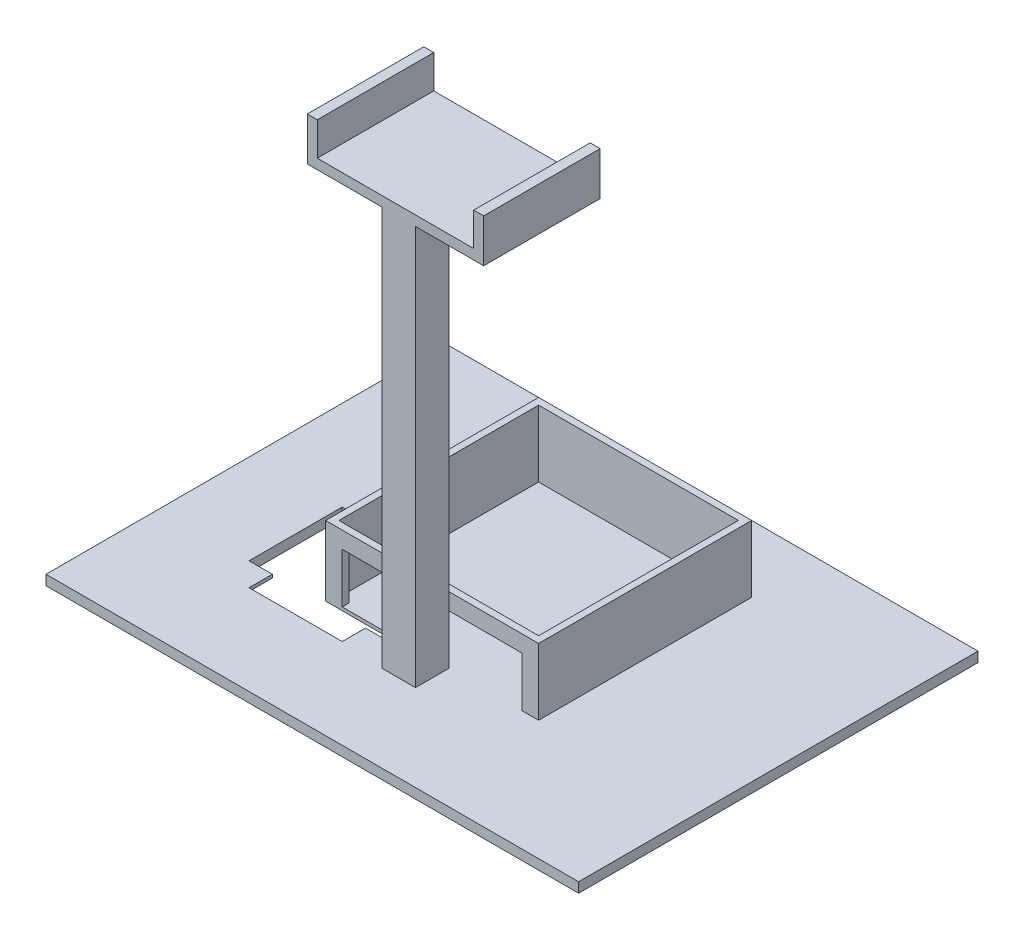
SolidWorks part; units mm, degrees
ref_plane "Front Plane" through (0, 0, 0) normal (0, 0, 1) x (1, 0, 0)
ref_plane "Top Plane" through (0, 0, 0) normal (0, 1, 0) x (1, 0, 0)
ref_plane "Right Plane" through (0, 0, 0) normal (1, 0, 0) x (0, 0, -1)
sketch "Sketch1" plane through (0, 0, 0) normal (0, 1, 0) x (1, 0, 0)
  line L1 (-80, -60) -> (80, -60)
  line L2 (-80, -60) -> (-80, 60)
  line L3 (-80, 60) -> (80, 60)
  line L4 (80, -60) -> (80, 60)
  line L5 (-80, -60) -> (80, 60) construction
  line L6 (-80, 60) -> (80, -60) construction
  point P0 (0, 0)
  dimension "D1" = 160
  dimension "D2" = 120
extrude "Boss-Extrude1" add sketch "Sketch1" along normal blind 3
sketch "Sketch2" plane through (0, 0, 0) normal (0, -1, 0) x (1, 0, 0)
  line L0 (0, 60) -> (0, 50) construction
  line L1 (-80, 60) -> (80, 60) construction
  line L2 (80, 60) -> (80, 50) construction
  line L3 (80, 60) -> (80, -60) construction
  line L4 (80, 50) -> (70, 50) construction
  line L5 (-80, 60) -> (-80, 50) construction
  line L6 (-80, -60) -> (-80, 60) construction
  line L7 (-80, 50) -> (-70, 50) construction
  line L8 (-80, 0) -> (-70, 0) construction
  line L9 (-80, -60) -> (-70, -60) construction
  line L10 (80, -60) -> (-80, -60) construction
  line L11 (-70, -60) -> (-70, -50) construction
  line L12 (80, 0) -> (70, 0) construction
  line L13 (80, -60) -> (70, -60) construction
  line L14 (70, -60) -> (70, -50) construction
  line L15 (0, -60) -> (0, -50) construction
  circle A0 centre (-70, 50) radius 5
  circle A1 centre (0, 50) radius 5
  circle A2 centre (70, 50) radius 5
  circle A3 centre (-70, 0) radius 5
  circle A4 centre (70, 0) radius 5
  circle A5 centre (-70, -50) radius 5
  circle A6 centre (0, -50) radius 5
  circle A7 centre (70, -50) radius 5
  dimension "D12" = 10
  dimension "D13" = 10
  dimension "D14" = 10
  dimension "D15" = 10
  dimension "D16" = 10
  dimension "D17" = 10
  dimension "D18" = 10
  dimension "D19" = 10
  dimension "D20" = 10
  dimension "D1" = 10
  dimension "D2" = 10
  dimension "D3" = 10
  dimension "D4" = 10
  dimension "D5" = 10
  dimension "D6" = 10
  dimension "D7" = 10
  dimension "D8" = 10
  dimension "D9" = 10
  dimension "D10" = 10
  dimension "D11" = 10
extrude "Cut-Extrude1" cut sketch "Sketch2" against normal blind 2
sketch "Sketch3" plane through (0, 0, 0) normal (0, -1, 0) x (1, 0, 0)
  line L0 (-80, 60) -> (-53, 60) construction
  line L1 (-80, 60) -> (80, 60) construction
  line L2 (-53, 60) -> (-53, 33) construction
  line L4 (-53, 33) -> (-11, 33)
  line L5 (-53, 33) -> (-53, -9)
  line L6 (-53, -9) -> (-11, -9)
  line L7 (-11, 33) -> (-11, -9)
  dimension "D1" = 27
  dimension "D2" = 27
  dimension "D3" = 42
  dimension "D4" = 42
extrude "Cut-Extrude2" cut sketch "Sketch3" against normal blind 2
sketch "Sketch4" plane through (0, 2, 0) normal (0, -1, 0) x (1, 0, 0)
  line L0 (-46, 33) -> (-18, 33)
  line L1 (-11, 33) -> (-53, 33) construction
  line L2 (-11, 33) -> (-53, 33) construction
  line L3 (-18, 33) -> (-18, 26)
  line L4 (-18, 26) -> (-11, 26)
  line L5 (-11, -9) -> (-11, 33) construction
  line L6 (-11, 26) -> (-11, -2)
  line L7 (-11, -9) -> (-11, 33) construction
  line L8 (-11, -2) -> (-18, -2)
  line L9 (-18, -2) -> (-18, -9)
  line L10 (-53, -9) -> (-11, -9) construction
  line L11 (-18, -9) -> (-46, -9)
  line L12 (-53, -9) -> (-11, -9) construction
  line L13 (-46, -9) -> (-46, -2)
  line L14 (-46, -2) -> (-53, -2)
  line L15 (-53, 33) -> (-53, -9) construction
  line L16 (-53, -2) -> (-53, 26)
  line L17 (-53, 33) -> (-53, -9) construction
  line L18 (-53, 26) -> (-46, 26)
  line L19 (-46, 26) -> (-46, 33)
  dimension "D1" = 7
  dimension "D2" = 7
  dimension "D3" = 7
  dimension "D4" = 7
  dimension "D5" = 7
  dimension "D6" = 7
  dimension "D7" = 7
  dimension "D8" = 7
extrude "Cut-Extrude3" cut sketch "Sketch4" against normal blind 1
sketch "Sketch5" plane through (0, 3, 0) normal (0, 1, 0) x (1, 0, 0)
  line L0 (0, 60) -> (0, 40) construction
  line L1 (80, 60) -> (-80, 60) construction
  line L2 (0, 40) -> (-32, 40)
  line L3 (-32, 40) -> (-32, -24)
  line L4 (-32, -24) -> (32, -24)
  line L5 (32, -24) -> (32, 40)
  line L6 (32, 40) -> (0, 40)
  dimension "D1" = 32
  dimension "D2" = 32
  dimension "D3" = 64
  dimension "D4" = 20
extrude "Boss-Extrude2" add sketch "Sketch5" along normal blind 20
sketch "Sketch6" plane through (0, 3, 0) normal (0, -1, 0) x (1, 0, 0)
  line L0 (-32, 24) -> (-11, 24)
  line L1 (-11, 24) -> (-11, -2)
  line L2 (-11, -2) -> (-18, -2)
  line L3 (-18, -2) -> (-18, -9)
  line L4 (-18, -9) -> (-32, -9)
  line L5 (-32, -9) -> (-32, 24)
extrude "Boss-Extrude3" add sketch "Sketch6" along normal blind 1
sketch "Sketch7" plane through (0, 23, 0) normal (0, 1, 0) x (1, 0, 0)
  line L0 (32, 40) -> (-32, 40) construction
  line L1 (-30, 38) -> (30, 38)
  line L2 (-30, 38) -> (-30, -22)
  line L3 (-30, -22) -> (30, -22)
  line L4 (30, 38) -> (30, -22)
  line L5 (32, -24) -> (32, 40) construction
  dimension "D1" = 2
  dimension "D2" = 2
  dimension "D3" = 60
  dimension "D4" = 60
extrude "Cut-Extrude4" cut sketch "Sketch7" against normal blind 20
sketch "Sketch8" plane through (0, 0, 24) normal (0, 0, 1) x (1, 0, 0)
  line L0 (-80, 3) -> (80, 3) construction
  line L1 (-27, 3) -> (27, 3)
  line L2 (-27, 3) -> (-27, 18)
  line L3 (-27, 18) -> (27, 18)
  line L4 (27, 3) -> (27, 18)
  line L5 (32, 23) -> (32, 3) construction
  line L6 (-32, 23) -> (-32, 2) construction
  dimension "D1" = 15
  dimension "D2" = 5
  dimension "D3" = 5
extrude "Cut-Extrude5" cut sketch "Sketch8" against normal up to next
sketch "Sketch9" plane through (0, 3, 0) normal (0, 1, 0) x (1, 0, 0)
  line L0 (-27, -24) -> (27, -24) construction
  line L1 (0, -24) -> (5, -24)
  line L2 (5, -24) -> (5, -34)
  line L3 (5, -34) -> (-5, -34)
  line L4 (-5, -24) -> (0, -24)
  line L5 (-5, -24) -> (-5, -34)
  dimension "D1" = 10
  dimension "D2" = 10
  dimension "D3" = 5
extrude "Boss-Extrude4" add sketch "Sketch9" along normal blind 120 contours L3 L5 L4 L1 L2
sketch "Sketch10" plane through (0, 123, 0) normal (0, 1, 0) x (1, 0, 0)
  line L0 (0, -34) -> (25.5, -34)
  line L1 (5, -34) -> (-5, -34) construction
  line L2 (25.5, -34) -> (25.5, 1)
  line L3 (25.5, 1) -> (-27.5, 1)
  line L4 (-27.5, 1) -> (-27.5, -34)
  line L5 (-27.5, -34) -> (0, -34)
  dimension "D1" = 35
  dimension "D2" = 25.5
  dimension "D3" = 53
extrude "Boss-Extrude5" add sketch "Sketch10" along normal blind 3
sketch "Sketch11" plane through (0, 126, 0) normal (0, 1, 0) x (1, 0, 0)
  line L0 (25.5, 1) -> (-27.5, 1) construction
  line L1 (25.5, -34) -> (22.5, -34)
  line L2 (25.5, -34) -> (25.5, 1)
  line L3 (25.5, 1) -> (22.5, 1)
  line L4 (22.5, -34) -> (22.5, 1)
  line L6 (-27.5, -34) -> (-24.5, -34)
  line L7 (-27.5, -34) -> (-27.5, 1)
  line L8 (-27.5, 1) -> (-24.5, 1)
  line L9 (-24.5, -34) -> (-24.5, 1)
  dimension "D1" = 3
  dimension "D2" = 3
extrude "Boss-Extrude6" add sketch "Sketch11" along normal blind 10
